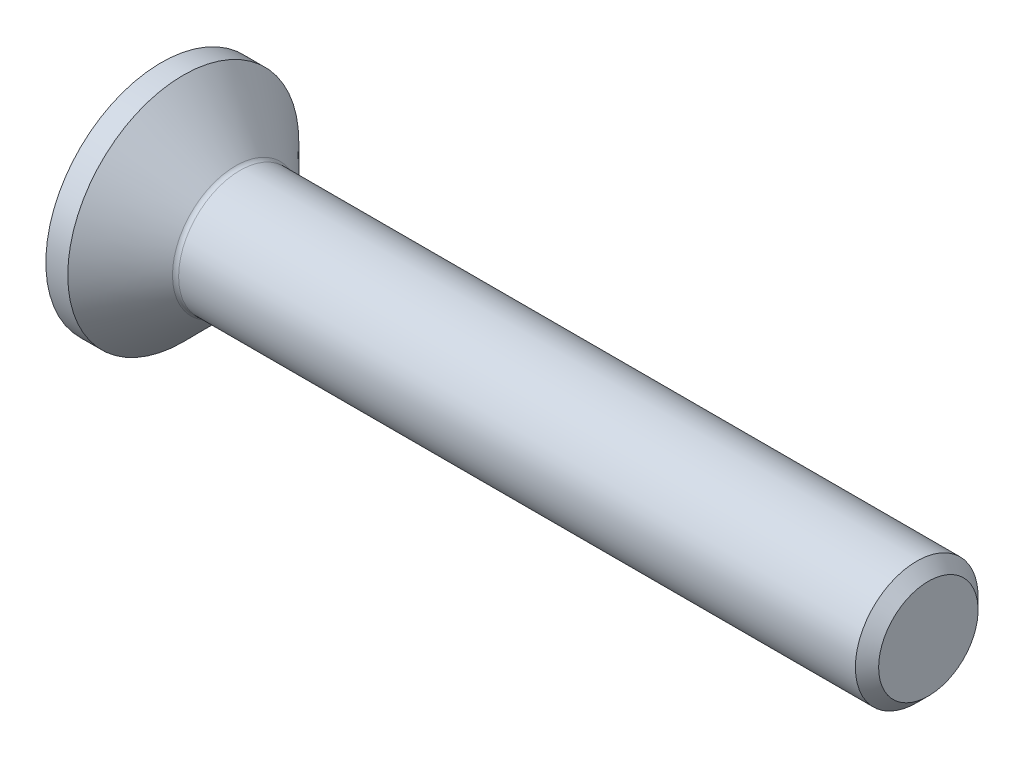
SolidWorks part; units mm, degrees
ref_plane "Front" through (0, 0, 0) normal (0, 0, 1) x (1, 0, 0)
ref_plane "Top" through (0, 0, 0) normal (0, 1, 0) x (1, 0, 0)
ref_plane "Right" through (0, 0, 0) normal (1, 0, 0) x (0, 0, -1)
sketch "Sketch1" plane through (0, 0, 0) normal (0, 0, 1) x (1, 0, 0)
  line L0 (0, 0) -> (0, 4.48)
  line L1 (0, 4.48) -> (2.48, 2)
  line L2 (2.48, 2) -> (25, 2)
  line L3 (25, 2) -> (25, 0)
  line L4 (25, 0) -> (0, 0)
  line L5 (-0.5871, 0) -> (5.4927, 0) construction
  dimension "l" = 25
  dimension "k" = 2.48
  dimension "d" = 4
  dimension "D1" = 45
revolve "Base" add sketch "Sketch1" angle 360 about L5
cosmetic thread "ThreadCosmetic1" parameters "b"=20, "D2"=3.242
sketch "Sketch2" plane through (0, 0, 0) normal (1, 0, 0) x (0, 0, -1)
  line L1 (1.4434, 0) -> (0.7217, 1.25)
  line L2 (0.7217, 1.25) -> (-0.7217, 1.25)
  line L3 (-0.7217, 1.25) -> (-1.4434, 0)
  line L4 (-1.4434, 0) -> (-0.7217, -1.25)
  line L5 (-0.7217, -1.25) -> (0.7217, -1.25)
  line L6 (0.7217, -1.25) -> (1.4434, 0)
  circle A0 centre (0, 0) radius 1.25 construction
  dimension "s" = 2.5
extrude "HexagonSocket" cut sketch "Sketch2" along normal blind 1.5
sketch "Sketch3" plane through (0, 0, 0) normal (0, 0, 1) x (1, 0, 0)
  line L0 (-0.4391, 0) -> (4.425, 0) construction
  line L1 (1.5, 0) -> (1.5, -1.25) construction
  line L2 (1.5, 1.25) -> (2.2217, 0)
  line L3 (2.2217, 0) -> (1.5, -1.25) construction
  line L4 (1.5, 1.25) -> (1.5, 0)
  line L5 (1.5, 0) -> (2.2217, 0)
  line L7 (1.5, 1.25) -> (1.5, 0) construction
  dimension "D1" = 120
revolve "Cut-Revolve1" cut sketch "Sketch3" angle 360 about L0
fillet "HeadFillet" radius 0.2 1 edges at (2.48, 0, 2)
chamfer "Chamfer" distance 0.379 angle 45 1 edges at (25, 0, 2)
sketch "Sketch4" plane through (0, 0, 0) normal (0, 1, 0) x (1, 0, 0)
  line L0 (11.8531, 0) -> (-2.694, 0) construction
  line L1 (-2, 8.765) -> (3, 8.765)
  line L2 (-2, 8.765) -> (-2, 3.765)
  line L3 (-2, 3.765) -> (3, 3.765)
  line L4 (3, 8.765) -> (3, 3.765)
  line L5 (0, 4.48) -> (0, -4.48) construction
  dimension "dk" = 7.53
  dimension "D2" = 2
  dimension "D3" = 5
  dimension "D4" = 5
revolve "Cut-Revolve2" cut sketch "Sketch4" angle 360 about L0
sketch "Sketch5" plane through (0, 0, 0) normal (0, 0, 1) x (1, 0, 0)
  line L0 (24.621, 1.6718) -> (24.8105, 2)
  line L1 (24.8105, 2) -> (24.8105, 2.379)
  line L2 (24.8105, 2.379) -> (24.4315, 2.379)
  line L3 (24.4315, 2.379) -> (24.4315, 2)
  line L4 (24.4315, 2) -> (24.621, 1.6718)
  line L5 (0, 0) -> (10.6885, 0) construction
  line L6 (24.621, 2) -> (24.621, -2) construction
  dimension "D1" = 4
  dimension "D2" = 0.379
revolve "Cut-Revolve10" [suppressed] cut sketch "Sketch5" angle 360 about L5
pattern_linear "LPattern10" [suppressed] count 44 spacing 0.4548 along (1, 0, 0)
equation "\"D1@Chamfer\" = (  \"d@Sketch1\" - \"D2@ThreadCosmetic1\" )  / 2"
equation "\"D1@Sketch5\" = \"d@Sketch1\""
equation "\"D2@Sketch5\" =  ( \"d@Sketch1\" - \"D2@ThreadCosmetic1\" )  / 2"
equation "\"D3@LPattern10\" = \"D2@Sketch5\" * 1.2"
equation "\"D1@LPattern10\" = \"b@ThreadCosmetic1\" / \"D3@LPattern10\""
